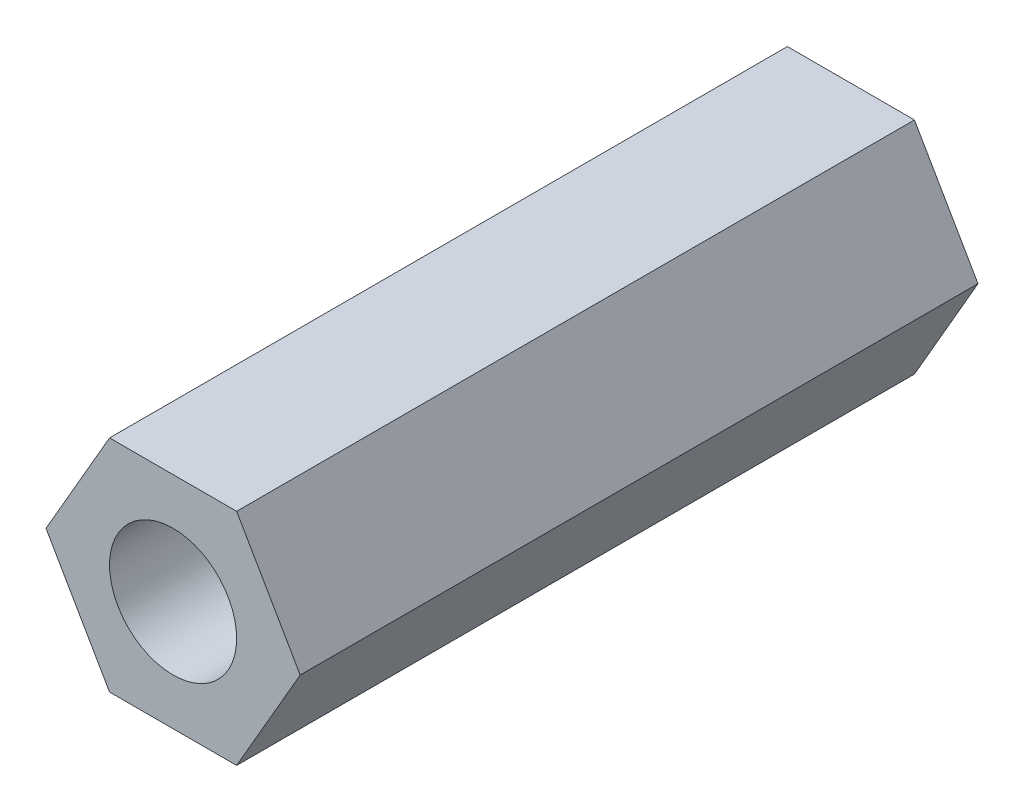
SolidWorks part; units mm, degrees
ref_plane "Alzado" through (0, 0, 0) normal (0, 0, 1) x (1, 0, 0)
ref_plane "Planta" through (0, 0, 0) normal (0, 1, 0) x (1, 0, 0)
ref_plane "Vista lateral" through (0, 0, 0) normal (1, 0, 0) x (0, 0, -1)
sketch "Croquis1" plane through (0, 0, 0) normal (0, 0, 1) x (1, 0, 0)
  line L0 (0, 0) -> (0.0003, 2.5981) construction
  line L1 (1.5003, 2.5979) -> (-1.4997, 2.5983)
  line L2 (-1.4997, 2.5983) -> (-3, 0.0004)
  line L3 (-3, 0.0004) -> (-1.5003, -2.5979)
  line L4 (-1.5003, -2.5979) -> (1.4997, -2.5983)
  line L5 (1.4997, -2.5983) -> (3, -0.0004)
  line L6 (3, -0.0004) -> (1.5003, 2.5979)
  circle A0 centre (0, 0) radius 2.5981 construction
  circle A1 centre (0, 0) radius 1.5
  dimension "D1" = 3
extrude "Saliente-Extruir1" add sketch "Croquis1" along normal blind 16
